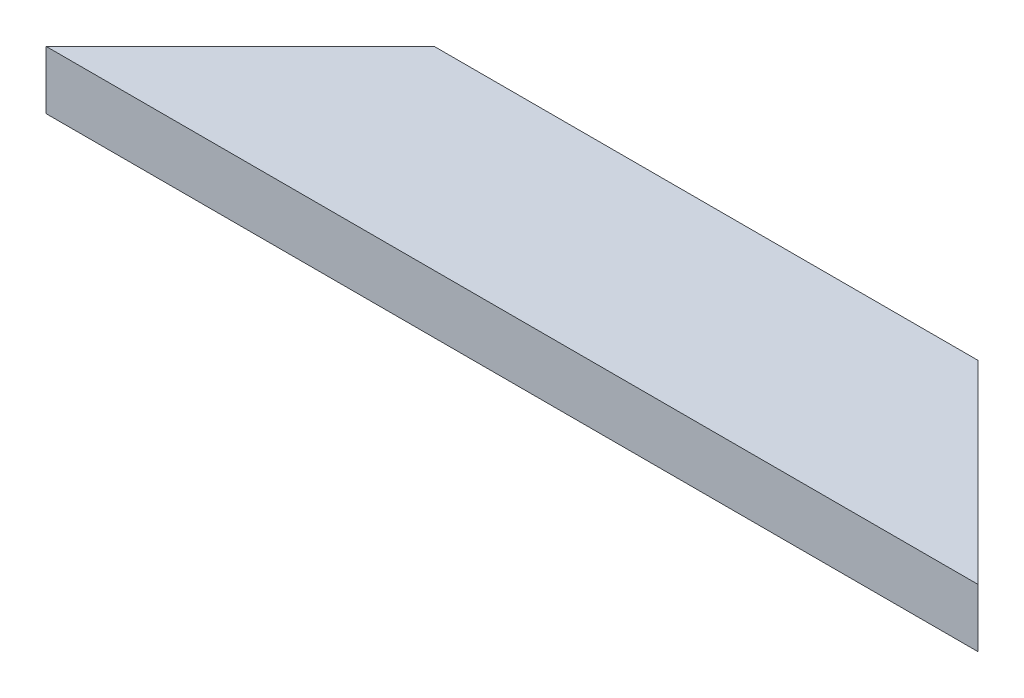
SolidWorks part; units mm, degrees
material "Pine"
ref_plane "Front Plane" through (0, 0, 0) normal (0, 0, 1) x (1, 0, 0)
ref_plane "Top Plane" through (0, 0, 0) normal (0, 1, 0) x (1, 0, 0)
ref_plane "Right Plane" through (0, 0, 0) normal (1, 0, 0) x (0, 0, -1)
sketch "Sketch1" plane through (0, 0, 0) normal (0, 1, 0) x (1, 0, 0)
  line L0 (-106.0606, 52.9788) -> (71.7394, 52.9788)
  line L1 (71.7394, 52.9788) -> (135.1688, -10.4505)
  line L2 (135.1688, -10.4505) -> (-169.4899, -10.4505)
  line L3 (-106.0606, 52.9788) -> (-169.4899, -10.4505)
  line L4 (-17.1606, 52.9788) -> (-17.1606, -10.5212)
  dimension "D1" = 45
  dimension "D2" = 45
extrude "Boss-Extrude1" add sketch "Sketch1" along normal blind 19.05 contours L2 L3 L0 L1
